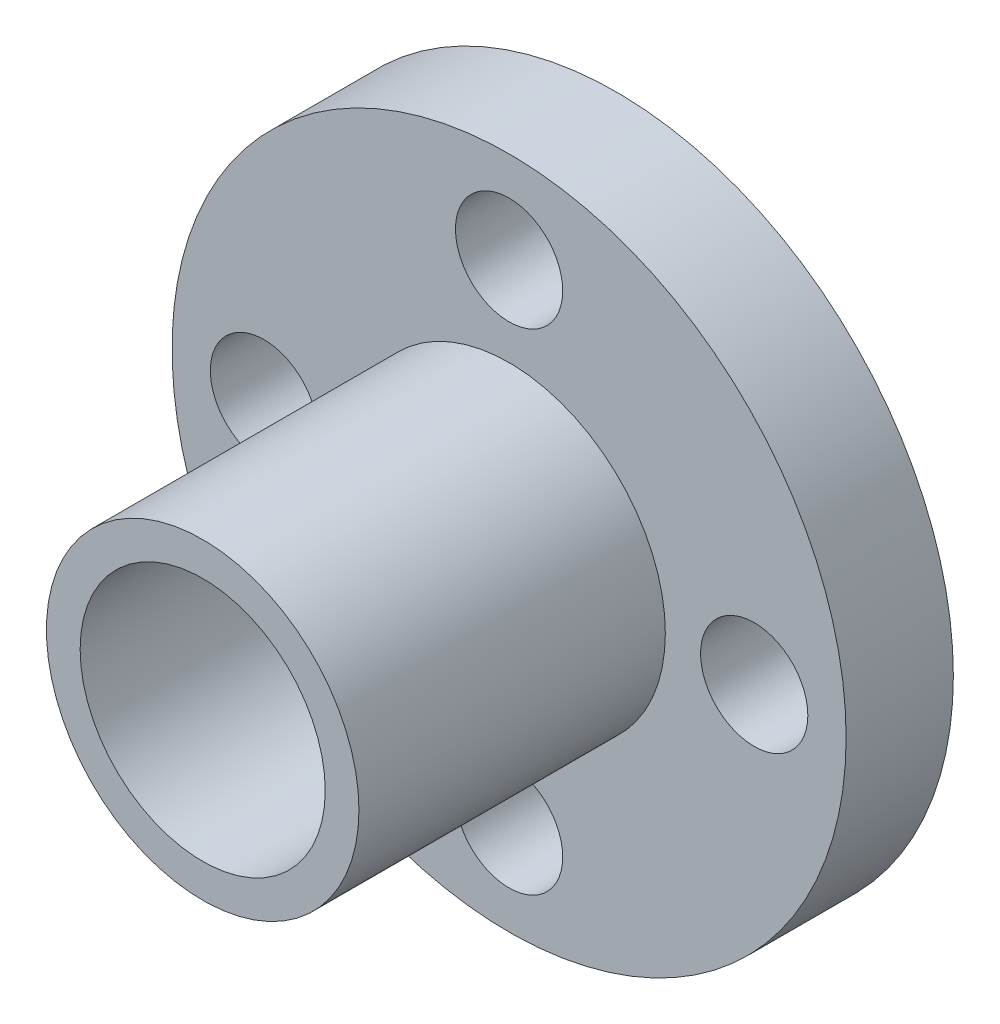
SolidWorks part; units mm, degrees
ref_plane "Alzado" through (0, 0, 0) normal (0, 0, 1) x (1, 0, 0)
ref_plane "Planta" through (0, 0, 0) normal (0, 1, 0) x (1, 0, 0)
ref_plane "Vista lateral" through (0, 0, 0) normal (1, 0, 0) x (0, 0, -1)
sketch "Croquis1" plane through (0, 0, 0) normal (0, 0, 1) x (1, 0, 0)
  circle A0 centre (0, 0) radius 11
  dimension "D1" = 22
extrude "Saliente-Extruir1" add sketch "Croquis1" along normal blind 3.5
sketch "Croquis2" plane through (0, 0, 3.5) normal (0, 0, 1) x (1, 0, 0)
  circle A0 centre (0, 0) radius 5.1
  dimension "D1" = 10.2
extrude "Saliente-Extruir2" add sketch "Croquis2" along normal blind 10
sketch "Croquis3" plane through (0, 0, 0) normal (0, 0, -1) x (-1, 0, 0)
  circle A0 centre (0, 0) radius 5.1
  dimension "D1" = 10.2
extrude "Saliente-Extruir3" add sketch "Croquis3" along normal blind 1.5
sketch "Croquis4" plane through (0, 0, 3.5) normal (0, 0, 1) x (1, 0, 0)
  line L0 (0, 0) -> (11, 0) construction
  circle A0 centre (0, 0) radius 11 construction
  circle A1 centre (8, 0) radius 1.75
  circle A2 centre (0, -8) radius 1.75
  circle A3 centre (-8, 0) radius 1.75
  circle A4 centre (0, 8) radius 1.75
  point P16 (0, 0)
  dimension "D1" = 3.5
  dimension "D2" = 8
  dimension "D3" = 4
extrude "Cortar-Extruir1" cut sketch "Croquis4" against normal through all
sketch "Croquis5" plane through (0, 0, 13.5) normal (0, 0, 1) x (1, 0, 0)
  circle A0 centre (0, 0) radius 4
  dimension "D1" = 8
extrude "Cortar-Extruir2" cut sketch "Croquis5" against normal through all
